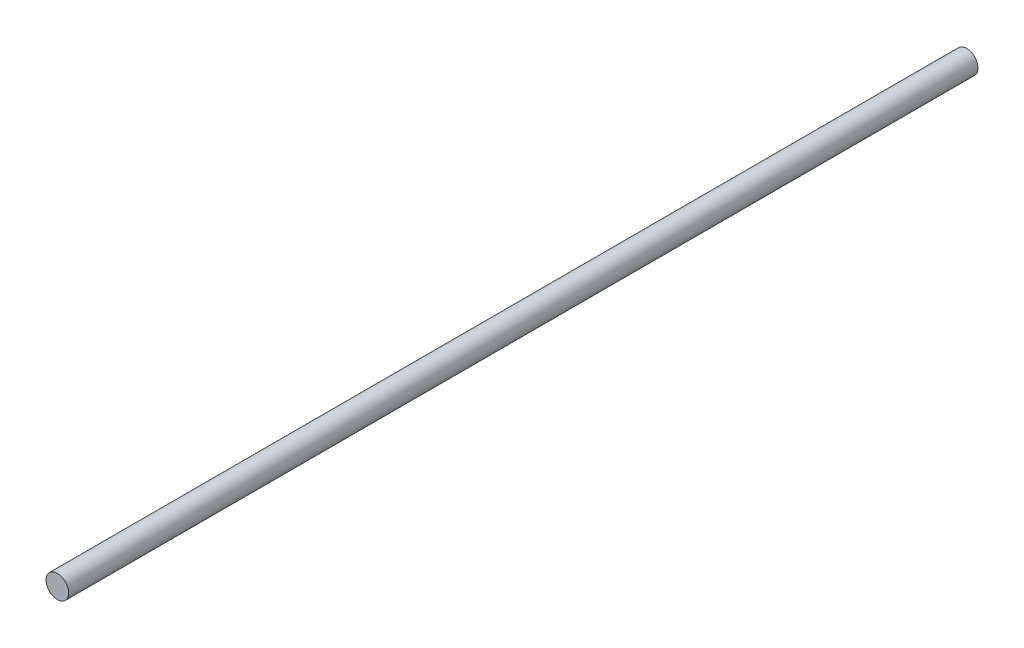
SolidWorks part; units mm, degrees
ref_plane "Front Plane" through (0, 0, 0) normal (0, 0, 1) x (1, 0, 0)
ref_plane "Top Plane" through (0, 0, 0) normal (0, 1, 0) x (1, 0, 0)
ref_plane "Right Plane" through (0, 0, 0) normal (1, 0, 0) x (0, 0, -1)
sketch "Sketch2" plane through (0, 0, 0) normal (0, 0, 1) x (1, 0, 0)
  circle A0 centre (0, 0) radius 1
  dimension "D1" = 2
extrude "Boss-Extrude1" add sketch "Sketch2" along normal blind 80
